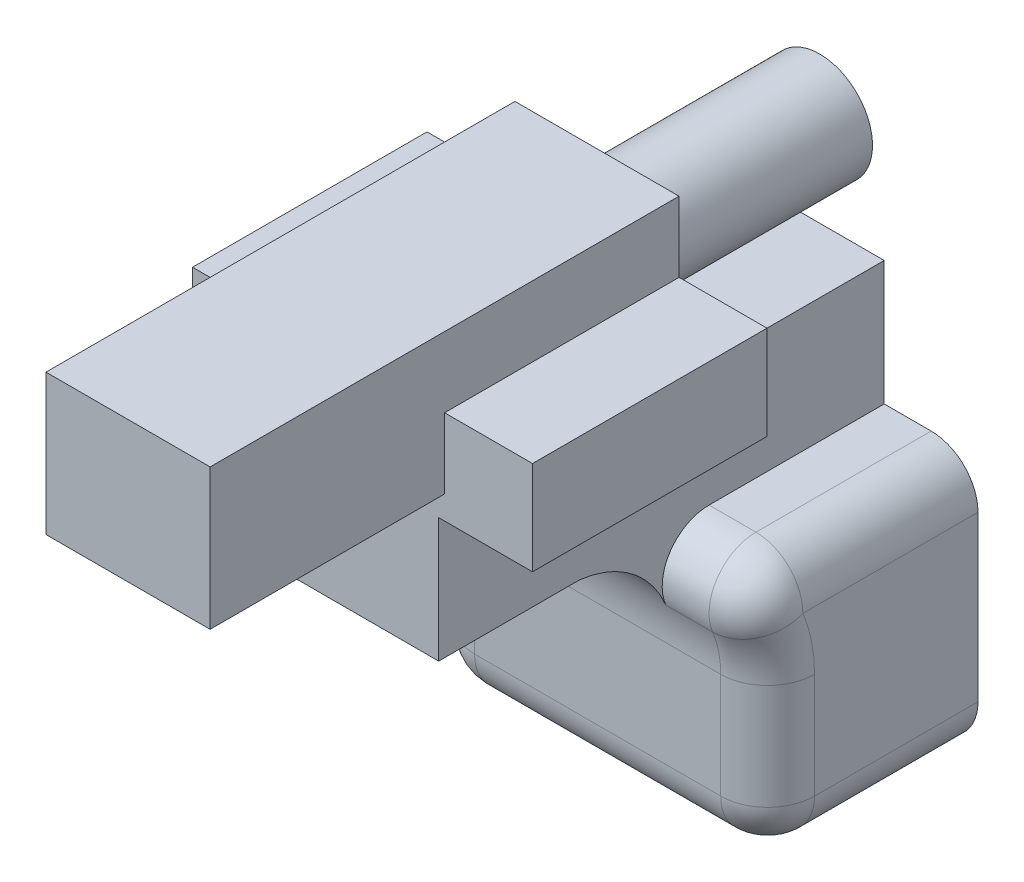
SolidWorks part; units mm, degrees
material "ABS"
ref_plane "Front Plane" through (0, 0, 0) normal (0, 0, 1) x (1, 0, 0)
ref_plane "Top Plane" through (0, 0, 0) normal (0, 1, 0) x (1, 0, 0)
ref_plane "Right Plane" through (0, 0, 0) normal (1, 0, 0) x (0, 0, -1)
sketch "Sketch1" plane through (0, 0, 0) normal (0, 0, 1) x (1, 0, 0)
  line L1 (2.75, 0) -> (2.75, 5.3)
  line L2 (2.75, 5.3) -> (6.75, 5.3)
  line L3 (6.75, 5.3) -> (6.75, 9.3)
  line L4 (6.75, 9.3) -> (3, 9.3)
  line L5 (-7.75, 9.3) -> (-7.75, 5.3)
  line L6 (-7.75, 5.3) -> (-3.75, 5.3)
  line L7 (-3.75, 5.3) -> (-3.75, 0)
  line L8 (-4, 9.3) -> (-4, 12.3)
  line L9 (-4, 12.3) -> (3, 12.3)
  line L10 (3, 12.3) -> (3, 9.3)
  line L11 (-4, 9.3) -> (-7.75, 9.3)
  line L12 (-3.75, 0) -> (-7.75, 0)
  line L13 (-7.75, 0) -> (-7.75, -11)
  line L14 (-7.75, -11) -> (6.75, -11)
  line L15 (6.75, -11) -> (6.75, 0)
  line L16 (2.75, 0) -> (6.75, 0)
  point P4 (0, 0)
  dimension "D1" = 6.5
  dimension "D2" = 4
  dimension "D3" = 5.3
  dimension "D4" = 4
  dimension "D5" = 3
  dimension "D7" = 4
  dimension "D8" = 11
  dimension "D6" = 7
extrude "Boss-Extrude1" add sketch "Sketch1" along normal blind 10
sketch "Sketch2" plane through (0, 0, 0) normal (0, 0, -1) x (-1, 0, 0)
  line L0 (-3, 12.3) -> (4, 12.3) construction
  line L1 (-2.75, 0) -> (-2.75, 5.3) construction
  line L2 (3.75, 5.3) -> (3.75, 0) construction
  line L3 (3.75, 0) -> (7.75, 0) construction
  line L6 (7.75, -11) -> (-6.75, -11) construction
  line L7 (-6.75, 0) -> (-2.75, 0) construction
  line L8 (-2.75, 0) -> (-2.75, 5.3)
  line L9 (3.75, 5.3) -> (3.75, 0)
  line L10 (3.75, 0) -> (7.75, 0)
  line L11 (7.75, 0) -> (7.75, -11)
  line L12 (7.75, -11) -> (-6.75, -11)
  line L13 (-6.75, -11) -> (-6.75, 0)
  line L14 (-6.75, 0) -> (-2.75, 0)
  line L15 (-2.75, 5.3) -> (3.75, 5.3)
  circle A0 centre (0, 9.3) radius 2.25
  dimension "D1" = 4.5
  dimension "D2" = 3
  dimension "D3" = 14.5
sketch "Sketch3" plane through (0, 0, 10) normal (0, 0, 1) x (1, 0, 0)
  line L1 (-7.75, -11) -> (6.75, -11)
  line L2 (-7.75, -11) -> (-7.75, 0)
  line L3 (-7.75, 0) -> (6.75, 0)
  line L4 (6.75, -11) -> (6.75, 0)
extrude "Cut-Extrude2" cut sketch "Sketch3" against normal blind 2
sketch "Sketch4" plane through (0, 0, 10) normal (0, 0, 1) x (1, 0, 0)
  line L2 (3, 12.3) -> (-4, 12.3) construction
  line L5 (3, 9.3) -> (3, 12.3)
  line L7 (3, 12.3) -> (-4, 12.3)
  line L9 (-4, 12.3) -> (-4, 9.3)
  line L12 (-4, 9.3) -> (-4, 6.3)
  line L13 (-4, 6.3) -> (3, 6.3)
  line L14 (3, 6.3) -> (3, 9.3)
  dimension "D2" = 6
extrude "Boss-Extrude2" add sketch "Sketch4" along normal blind 10
extrude "Boss-Extrude4" add sketch "Sketch2" along normal blind 9
sketch "Sketch6" plane through (6.75, 0, 0) normal (1, 0, 0) x (0, 0, -1)
  line L0 (-8, 0) -> (-4, 0)
  line L1 (0.0277, -4.5) -> (0.0277, -11)
  line L2 (-8, -11) -> (9, -11) construction
  line L3 (0.0277, -11) -> (-8, -11)
  line L4 (-8, -11) -> (-8, 0)
  arc A0 (-4, 0) -> (0, -5) centre (-4.5, -4.5) cw
extrude "Cut-Extrude5" cut sketch "Sketch6" against normal through all
fillet "Fillet1" radius 2 11 edges at (6.75, 0, -2.5) (-7.75, 0, -2.5) (-7.75, -11, -4.5138) (6.75, -11, -4.5138) (-5.75, 0, 4) (4.75, 0, 4) (6.75, -1.4804, 1.1263) (-7.75, -1.4804, 1.1263) (6.75, -7.75, -0.0277) (-7.75, -7.75, -0.0277) (-0.5, -11, -0.0277)
equation "\"D3@Sketch1\"=3.8+1.5"
